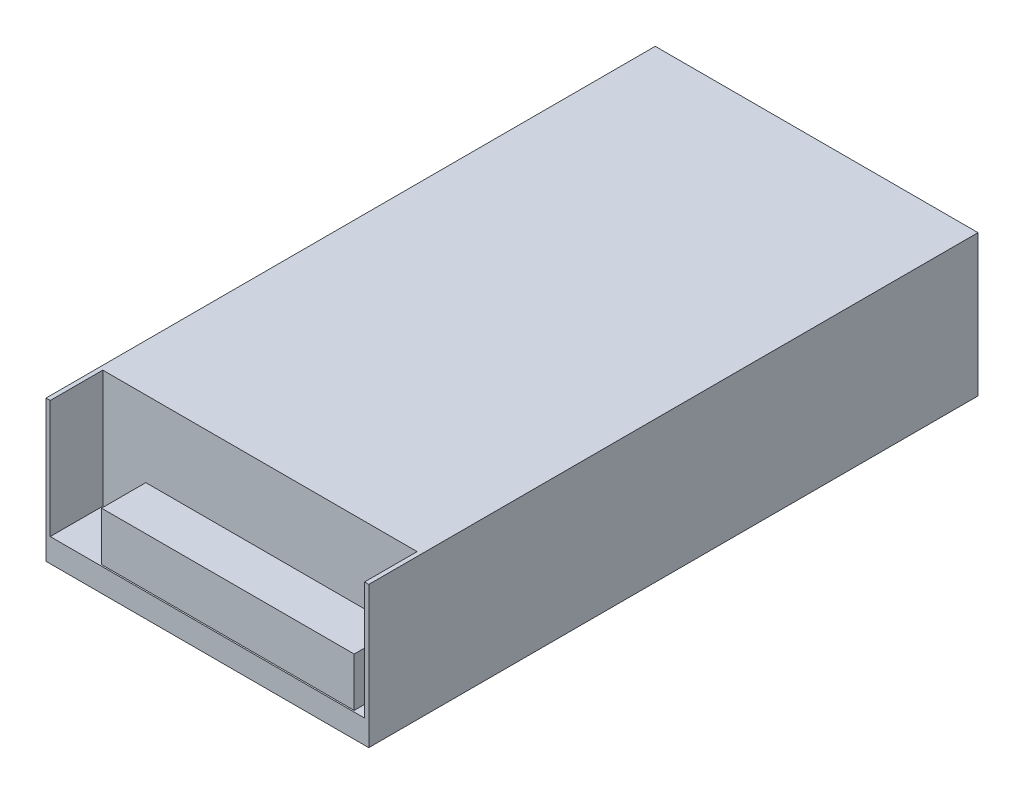
SolidWorks part; units mm, degrees
ref_plane "Front Plane" through (0, 0, 0) normal (0, 0, 1) x (1, 0, 0)
ref_plane "Top Plane" through (0, 0, 0) normal (0, 1, 0) x (1, 0, 0)
ref_plane "Right Plane" through (0, 0, 0) normal (1, 0, 0) x (0, 0, -1)
sketch "Sketch1" plane through (0, 0, 0) normal (0, 1, 0) x (1, 0, 0)
  line L1 (0, 0) -> (113.03, 0)
  line L2 (0, 0) -> (0, 213.36)
  line L3 (0, 213.36) -> (113.03, 213.36)
  line L4 (113.03, 0) -> (113.03, 213.36)
  dimension "D1" = 113.03
  dimension "D2" = 213.36
extrude "Boss-Extrude1" add sketch "Sketch1" along normal blind 49.53
sketch "Sketch2" plane through (0, 49.53, 0) normal (0, 1, 0) x (1, 0, 0)
  line L0 (0, 0) -> (113.03, 0) construction
  line L1 (1.4732, 0) -> (111.5568, 0)
  line L2 (1.4732, 0) -> (1.4732, 18.415)
  line L3 (1.4732, 18.415) -> (111.5568, 18.415)
  line L4 (111.5568, 0) -> (111.5568, 18.415)
  line L5 (0, 213.36) -> (0, 0) construction
  line L6 (113.03, 0) -> (113.03, 213.36) construction
  dimension "D1" = 1.4732
  dimension "D2" = 1.4732
  dimension "D3" = 18.415
extrude "Cut-Extrude1" cut sketch "Sketch2" against normal blind 41.275
sketch "Sketch3" plane through (0, 8.255, 0) normal (0, 1, 0) x (1, 0, 0)
  line L0 (111.5568, 0) -> (111.5568, 18.415) construction
  line L1 (18.9484, 0.508) -> (107.4166, 0.508)
  line L2 (18.9484, 0.508) -> (18.9484, 16.002)
  line L3 (18.9484, 16.002) -> (107.4166, 16.002)
  line L4 (107.4166, 0.508) -> (107.4166, 16.002)
  line L5 (1.4732, 0) -> (111.5568, 0) construction
  dimension "D1" = 88.4682
  dimension "D2" = 15.494
  dimension "D3" = 4.1402
  dimension "D4" = 0.508
extrude "Boss-Extrude2" add sketch "Sketch3" along normal blind 17.0942
sketch "Sketch4" plane through (0, 0, 0) normal (0, -1, 0) x (1, 0, 0)
  line L0 (113.03, -213.36) -> (0, -213.36) construction
  line L1 (31.515, -30.86) -> (81.515, -30.86) construction
  line L2 (31.515, -30.86) -> (31.515, -180.86) construction
  line L3 (31.515, -180.86) -> (81.515, -180.86) construction
  line L4 (81.515, -30.86) -> (81.515, -180.86) construction
  line L6 (56.515, -213.36) -> (56.515, 0) construction
  line L7 (0, 0) -> (113.03, 0) construction
  circle A0 centre (81.515, -180.86) radius 1.5875
  circle A1 centre (31.515, -180.86) radius 1.5875
  circle A2 centre (81.515, -30.86) radius 1.5875
  circle A3 centre (31.515, -30.86) radius 1.5875
  point P14 (56.515, -180.86)
  point P15 (0, 0)
  dimension "D3" = 3.175
  dimension "D1" = 50
  dimension "D2" = 150
  dimension "D4" = 32.5
extrude "Cut-Extrude2" cut sketch "Sketch4" against normal blind 5
ref_plane "Plane1" through (0, 0, -106.68) normal (0, 0, 1) x (1, 0, 0)
equation "\"D2@Sketch2\"=\"D1@Sketch2\""
